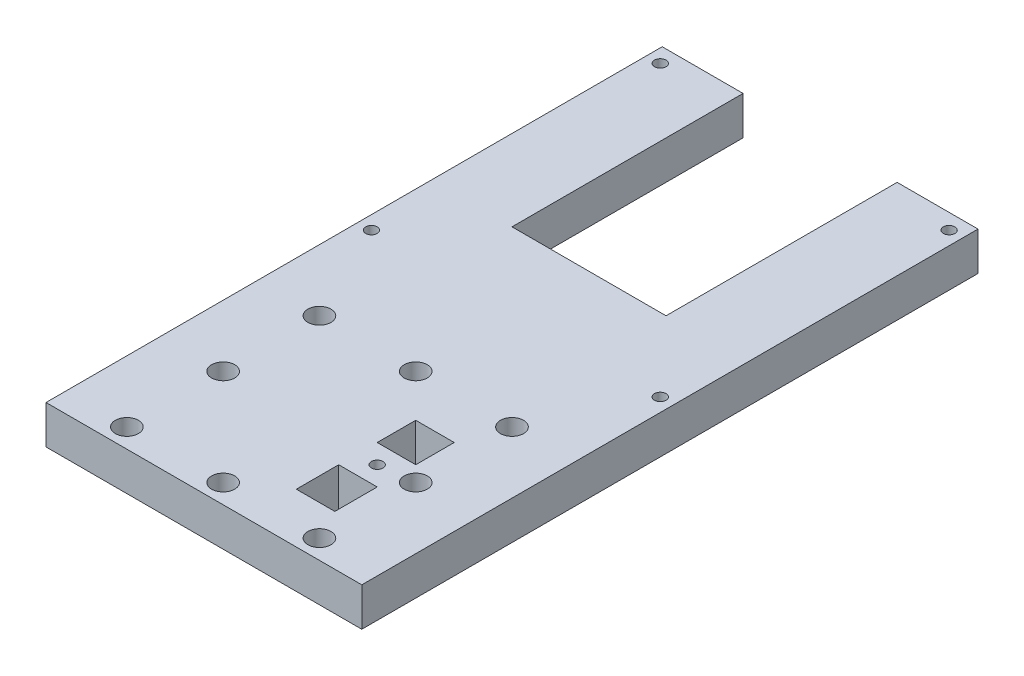
SolidWorks part; units mm, degrees
ref_plane "Front Plane" through (0, 0, 0) normal (0, 0, 1) x (1, 0, 0)
ref_plane "Top Plane" through (0, 0, 0) normal (0, 1, 0) x (1, 0, 0)
ref_plane "Right Plane" through (0, 0, 0) normal (1, 0, 0) x (0, 0, -1)
sketch "Sketch1" plane through (0, 0, 0) normal (0, 1, 0) x (1, 0, 0)
  line L0 (-33.0308, -9.7441) -> (16.9692, -9.7441) construction
  line L1 (32.9692, -64.7441) -> (-49.0308, -64.7441)
  line L2 (32.9692, -64.7441) -> (32.9692, 95.2559)
  line L3 (32.9692, 95.2559) -> (11.9692, 95.2559)
  line L4 (-49.0308, -64.7441) -> (-49.0308, 95.2559)
  line L5 (-45.5308, 16.2559) -> (29.4692, 16.2559) construction
  line L6 (-28.0308, 95.2559) -> (-49.0308, 95.2559)
  line L8 (-28.0308, 95.2559) -> (-28.0308, 35.2559)
  line L9 (-28.0308, 35.2559) -> (11.9692, 35.2559)
  line L10 (11.9692, 95.2559) -> (11.9692, 35.2559)
  line L11 (7.9692, -30.7441) -> (7.9692, -40.7441) construction
  line L12 (12.9692, -51.7441) -> (2.9692, -51.7441)
  line L13 (12.9692, -51.7441) -> (12.9692, -40.7441)
  line L14 (12.9692, -40.7441) -> (2.9692, -40.7441)
  line L15 (2.9692, -51.7441) -> (2.9692, -40.7441)
  line L16 (12.9692, -30.7441) -> (2.9692, -30.7441)
  line L17 (12.9692, -30.7441) -> (12.9692, -20.7441)
  line L18 (12.9692, -20.7441) -> (2.9692, -20.7441)
  line L19 (2.9692, -30.7441) -> (2.9692, -20.7441)
  circle A0 centre (-33.0308, -59.7441) radius 3
  circle A1 centre (16.9692, -59.7441) radius 3
  circle A2 centre (16.9692, -9.7441) radius 3
  circle A3 centre (-33.0308, -9.7441) radius 3
  circle A4 centre (-45.5308, 91.2559) radius 1.5
  circle A5 centre (29.4692, 91.2559) radius 1.5
  circle A6 centre (29.4692, 16.2559) radius 1.5
  circle A7 centre (-45.5308, 16.2559) radius 1.5
  circle A8 centre (-8.0308, -9.7441) radius 3
  circle A9 centre (-33.0308, -34.7441) radius 3
  circle A10 centre (16.9692, -34.7441) radius 3
  circle A11 centre (-8.0308, -59.7441) radius 3
  circle A12 centre (7.9692, -35.7441) radius 1.5
  point P6 (-8.0308, -9.7441)
  point P7 (-8.0308, -64.7441)
  dimension "D3" = 6
  dimension "D8" = 50
  dimension "D9" = 5
  dimension "D10" = 3
  dimension "D16" = 6
  dimension "D17" = 6
  dimension "D18" = 6
  dimension "D19" = 6
  dimension "D20" = 25
  dimension "D21" = 3
  dimension "D1" = 160
  dimension "D2" = 82
  dimension "D6" = 16
  dimension "D7" = 50
  dimension "D13" = 4
  dimension "D14" = 40
  dimension "D15" = 60
  dimension "D4" = 2
  dimension "D5" = 2
  dimension "D11" = 2
  dimension "D12" = 2
extrude "Boss-Extrude1" add sketch "Sketch1" along normal blind 10
hole_wizard "M3x0.5 Tapped Hole1" positions "Sketch3" profile "Sketch4" tap size "M3x0.5" standard "BSI"
sketch "Sketch3" plane through (0, 10, 0) normal (0, 1, 0) x (1, 0, 0)
  point P0 (-45.5308, 91.2559)
  point P3 (29.4692, 91.2559)
  point P6 (-45.5308, 16.2559)
  point P9 (29.4692, 16.2559)
sketch "Sketch4" plane through (-45.5308, 10, -91.2559) normal (1, 0, 0) x (0, 0, 1)
  line L0 (0, 0) -> (0, 10)
  line L1 (0, 10) -> (1.25, 10)
  line L2 (1.25, 10) -> (1.25, 0)
  line L5 (1.25, 0) -> (0, 0)
  line L11 (0, -6.35) -> (0, 107.95) construction
  dimension "Thru Tap Drill Dia." = 2.5
  dimension "Thru Tap Drill Depth" = 10
